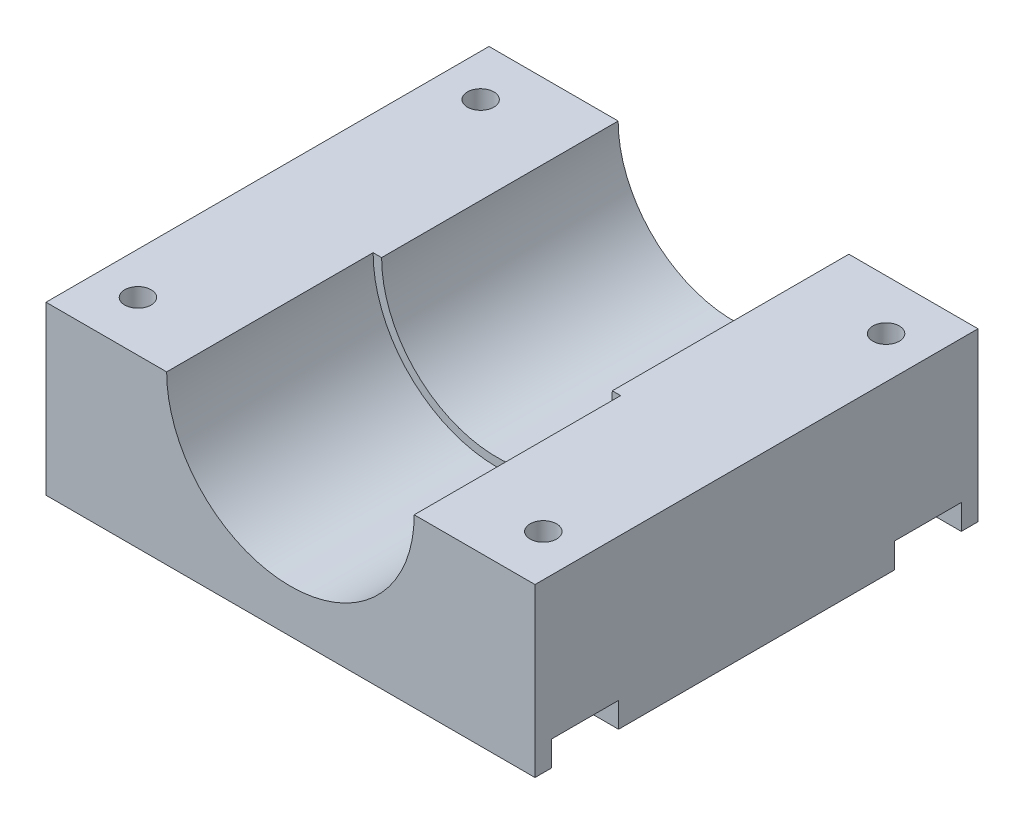
SolidWorks part; units mm, degrees
ref_plane "Alzado" through (0, 0, 0) normal (0, 0, 1) x (1, 0, 0)
ref_plane "Planta" through (0, 0, 0) normal (0, 1, 0) x (1, 0, 0)
ref_plane "Vista lateral" through (0, 0, 0) normal (1, 0, 0) x (0, 0, -1)
sketch "Sketch1" plane through (0, 0, 0) normal (0, 0, 1) x (1, 0, 0)
  line L1 (0, -13.6092) -> (58.5, -13.6092)
  line L2 (0, -13.6092) -> (0, 6.3908)
  line L3 (0, 6.3908) -> (58.5, 6.3908)
  line L4 (58.5, -13.6092) -> (58.5, 6.3908)
  dimension "D1" = 58.5
  dimension "D2" = 20
extrude "Boss-Extrude1" add sketch "Sketch1" along normal blind 53
sketch "Sketch3" plane through (0, 0, 53) normal (0, 0, 1) x (1, 0, 0)
  line L1 (14.4342, 6.3908) -> (44.05, 6.3908)
  arc A1 (14.4342, 6.3908) -> (44.05, 6.3908) centre (29.2421, 6.3908) ccw
extrude "Cut-Extrude2" cut sketch "Sketch3" against normal blind 24.7
ref_plane "Plane1" through (14.4342, 6.3908, 28.3) normal (-1, 0, 0) x (0, 0, 1)
sketch "Sketch5" plane through (0, 0, 0) normal (0, 0, -1) x (-1, 0, 0)
  line L1 (-43.05, 6.3908) -> (-15.45, 6.3908)
  arc A0 (-43.05, 6.3908) -> (-15.45, 6.3908) centre (-29.25, 6.3908) ccw
  dimension "D1" = 27.6
extrude "Cut-Extrude3" cut sketch "Sketch5" against normal blind 32.4
sketch "Sketch6" plane through (0, 0, 53) normal (0, 0, 1) x (1, 0, 0)
  line L0 (58.5, 2.6291) -> (49, 2.6291)
  line L1 (58.5, -13.6092) -> (58.5, 6.3908) construction
  line L2 (0, 2.6291) -> (9.5, 2.6291)
  line L3 (58.5, 2.6291) -> (58.5, -13.6092)
  line L4 (58.5, -13.6092) -> (0, -13.6092)
  line L5 (0, -13.6092) -> (0, 2.6291)
  arc A0 (49, 2.6291) -> (9.5, 2.6291) centre (29.25, 7.7188) cw
  dimension "D1" = 9.5
  dimension "D2" = 9.5
sketch "Sketch8" plane through (0, -13.6092, 0) normal (0, -1, 0) x (-1, 0, 0)
  line L0 (-58.5, -53) -> (-58.5, 0) construction
  line L1 (-58.5, -2) -> (-48.5, -2)
  line L2 (-58.5, -2) -> (-58.5, -10)
  line L3 (-58.5, -10) -> (-48.5, -10)
  line L4 (-48.5, -2) -> (-48.5, -10)
  line L5 (0, 0) -> (-58.5, 0) construction
  dimension "D1" = 8
  dimension "D2" = 2
  dimension "D4" = 0
extrude "Cut-Extrude6" cut sketch "Sketch8" against normal blind 3
sketch "Sketch7" plane through (0, -13.6092, 0) normal (0, -1, 0) x (-1, 0, 0)
  line L0 (-58.5, -53) -> (0, -53) construction
  line L1 (0, 0) -> (-58.5, 0) construction
  line L2 (-58.5, -2) -> (-58.5, -10) construction
  line L3 (0, -53) -> (0, 0) construction
  line L4 (-58.5, -53) -> (-58.5, -10) construction
  circle A0 centre (-53.5, -47) radius 1.585
  circle A1 centre (-53.5, -6) radius 1.585
  circle A2 centre (-5, -6) radius 1.585
  circle A3 centre (-5, -47) radius 1.585
  dimension "D1" = 3.17
  dimension "D2" = 3.17
  dimension "D3" = 3.17
  dimension "D4" = 3.17
  dimension "D5" = 6
  dimension "D6" = 6
  dimension "D7" = 6
  dimension "D8" = 6
  dimension "D9" = 5
  dimension "D10" = 5
  dimension "D11" = 5
  dimension "D12" = 5
extrude "Cut-Extrude5" cut sketch "Sketch7" against normal blind 92.5
ref_plane "Plane2" through (29.25, 0, 0) normal (-1, 0, 0) x (0, 0, 1)
ref_plane "Plane3" through (0, 0, 26.5) normal (0, 0, 1) x (1, 0, 0)
mirror "Mirror1" about plane through (0, 0, 26.5) normal (0, 0, 1) of "Cut-Extrude6" second plane through (29.25, 0, 0) second plane normal (-1, 0, 0)
